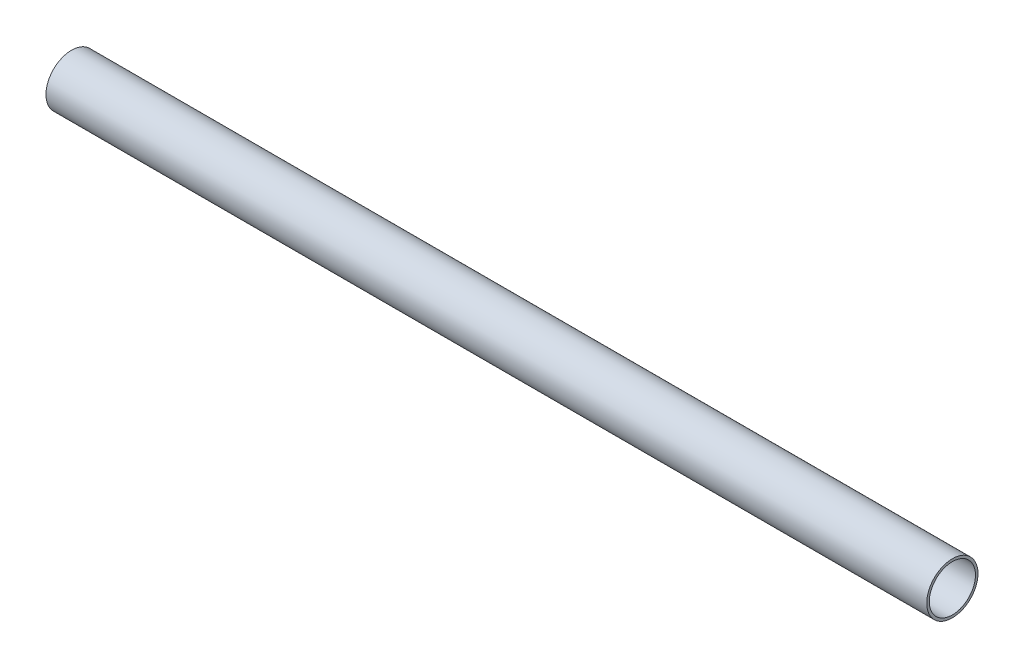
SolidWorks part; units mm, degrees
material "ASTM A36 Steel"
ref_plane "Front Plane" through (0, 0, 0) normal (0, 0, 1) x (1, 0, 0)
ref_plane "Top Plane" through (0, 0, 0) normal (0, 1, 0) x (1, 0, 0)
ref_plane "Right Plane" through (0, 0, 0) normal (1, 0, 0) x (0, 0, -1)
sketch "Sketch1" plane through (0, 0, 0) normal (1, 0, 0) x (0, 0, -1)
  circle A1 centre (0, 0) radius 30.15
  circle A2 centre (0, 0) radius 27.15
  dimension "D1" = 60.3
  dimension "D2" = 3
extrude "Boss-Extrude1" add sketch "Sketch1" along normal blind 1036
